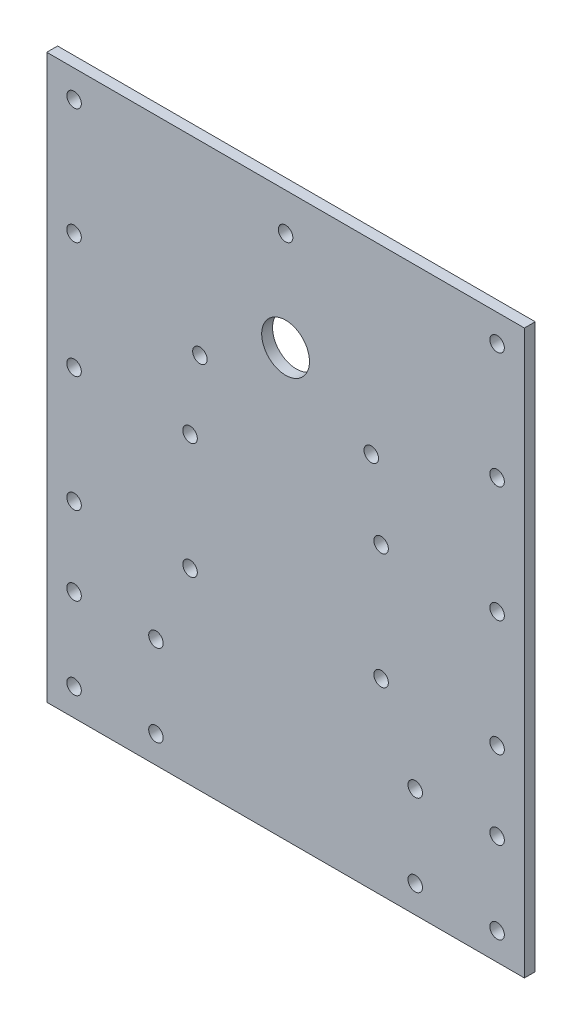
SolidWorks part; units mm, degrees
ref_plane "Front Plane" through (0, 0, 0) normal (0, 0, 1) x (1, 0, 0)
ref_plane "Top Plane" through (0, 0, 0) normal (0, 1, 0) x (1, 0, 0)
ref_plane "Right Plane" through (0, 0, 0) normal (1, 0, 0) x (0, 0, -1)
sketch "Sketch1" plane through (0, 0, 0) normal (0, 0, 1) x (1, 0, 0)
  line L0 (0, 82.5) -> (0, -82.5) construction
  line L1 (-70, -82.5) -> (70, -82.5)
  line L2 (-70, -82.5) -> (-70, 82.5)
  line L3 (-70, 82.5) -> (70, 82.5)
  line L4 (70, -82.5) -> (70, 82.5)
  line L5 (-70, -82.5) -> (70, 82.5) construction
  line L6 (-70, 82.5) -> (70, -82.5) construction
  line L7 (-50, -78.3304) -> (-50, -60.5714) construction
  line L10 (-62, -62.5) -> (-36.3402, -62.5) construction
  circle A0 centre (0, 42.5) radius 33.35 construction
  circle A1 centre (0, 42.5) radius 29 construction
  circle A2 centre (0, 71.5) radius 2.125
  circle A3 centre (25.1147, 28) radius 2.125
  circle A4 centre (-25.1147, 28) radius 2.125
  circle A10 centre (0, 42.5) radius 7
  circle A11 centre (-62, -74.5) radius 2.125
  circle A12 centre (-38, -74.5) radius 2.125
  circle A13 centre (-38, -50.5) radius 2.125
  circle A14 centre (-62, -50.5) radius 2.125
  circle A15 centre (38, -74.5) radius 2.125
  circle A16 centre (62, -74.5) radius 2.125
  circle A17 centre (62, -50.5) radius 2.125
  circle A18 centre (38, -50.5) radius 2.125
  point P0 (0, 0)
  point P19 (0, 42.5)
  dimension "D3" = 66.7
  dimension "D4" = 40
  dimension "D5" = 58
  dimension "D6" = 4.25
  dimension "D8" = 4.25
  dimension "D9" = 8
  dimension "D10" = 8
  dimension "D12" = 14
  dimension "D1" = 140
  dimension "D2" = 165
  dimension "D11" = 12
  dimension "D13" = 12
  dimension "D7" = 3
extrude "Boss-Extrude1" add sketch "Sketch1" along normal blind 3.175
sketch "Sketch2" plane through (0, 0, 3.175) normal (0, 0, 1) x (1, 0, 0)
  line L0 (70, 82.5) -> (-70, 82.5) construction
  line L1 (-70, 82.5) -> (-70, -82.5) construction
  line L2 (0, 82.5) -> (0, -82.5) construction
  line L3 (-70, -82.5) -> (70, -82.5) construction
  circle A0 centre (-62, 74.5) radius 2.125
  circle A1 centre (-62, 40.5) radius 2.125
  circle A2 centre (-62, 6.5) radius 2.125
  circle A3 centre (-62, -27.5) radius 2.125
  circle A4 centre (-28, 6.5) radius 2.125
  circle A5 centre (-28, -27.5) radius 2.125
  circle A6 centre (28, -27.5) radius 2.125
  circle A7 centre (28, 6.5) radius 2.125
  circle A8 centre (62, -27.5) radius 2.125
  circle A9 centre (62, 6.5) radius 2.125
  circle A10 centre (62, 40.5) radius 2.125
  circle A11 centre (62, 74.5) radius 2.125
  dimension "D1" = 4.25
  dimension "D2" = 8
  dimension "D3" = 8
  dimension "D4" = 4
  dimension "D5" = 2
extrude "Cut-Extrude1" cut sketch "Sketch2" against normal through all
